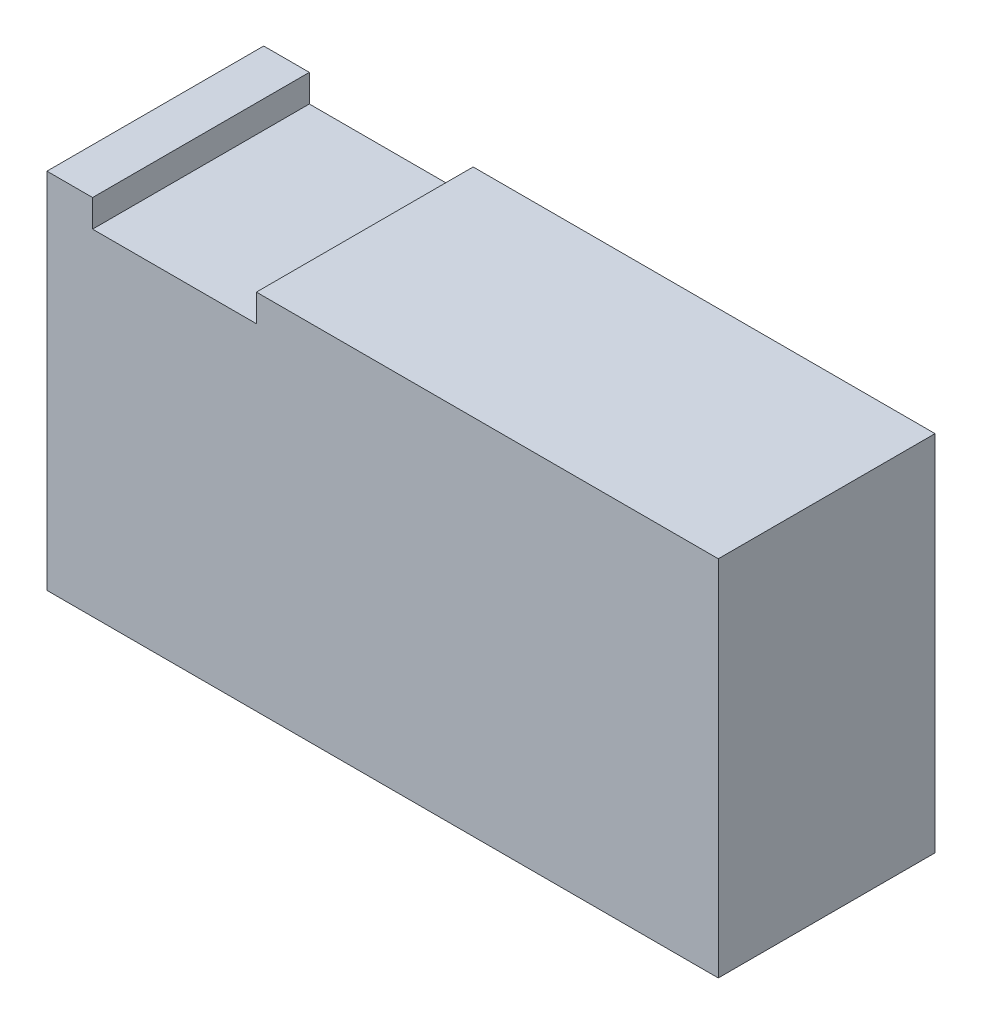
SolidWorks part; units mm, degrees
ref_plane "Спереди" through (0, 0, 0) normal (0, 0, 1) x (1, 0, 0)
ref_plane "Сверху" through (0, 0, 0) normal (0, 1, 0) x (1, 0, 0)
ref_plane "Справа" through (0, 0, 0) normal (1, 0, 0) x (0, 0, -1)
other "Configuration Table"
sketch "основание" plane through (0, 0, 0) normal (0, 1, 0) x (1, 0, 0)
  line L1 (-31.25, -10.09) -> (31.25, -10.09)
  line L2 (-31.25, -10.09) -> (-31.25, 10.09)
  line L3 (-31.25, 10.09) -> (31.25, 10.09)
  line L4 (31.25, -10.09) -> (31.25, 10.09)
  line L5 (-31.25, -10.09) -> (31.25, 10.09) construction
  line L6 (-31.25, 10.09) -> (31.25, -10.09) construction
  point P0 (0, 0)
  dimension "D1" = 20.18
  dimension "D2" = 62.5
extrude "Бобышка-Вытянуть1" add sketch "основание" along normal blind 33.8
sketch "Эскиз5" plane through (0, 33.8, 0) normal (0, 1, 0) x (1, 0, 0)
sketch "Эскиз6" plane through (0, 33.8, 0) normal (0, 1, 0) x (1, 0, 0)
  line L0 (31.25, 10.09) -> (-31.25, 10.09) construction
  line L1 (-27, 10.09) -> (-11.75, 10.09)
  line L2 (-27, 10.09) -> (-27, -10.09)
  line L3 (-27, -10.09) -> (-11.75, -10.09)
  line L4 (-11.75, 10.09) -> (-11.75, -10.09)
  line L5 (-31.25, -10.09) -> (31.25, -10.09) construction
  dimension "D1" = 15.25
  dimension "D2" = 4.25
extrude "Вырез-Вытянуть1" cut sketch "Эскиз6" against normal blind 2.55
